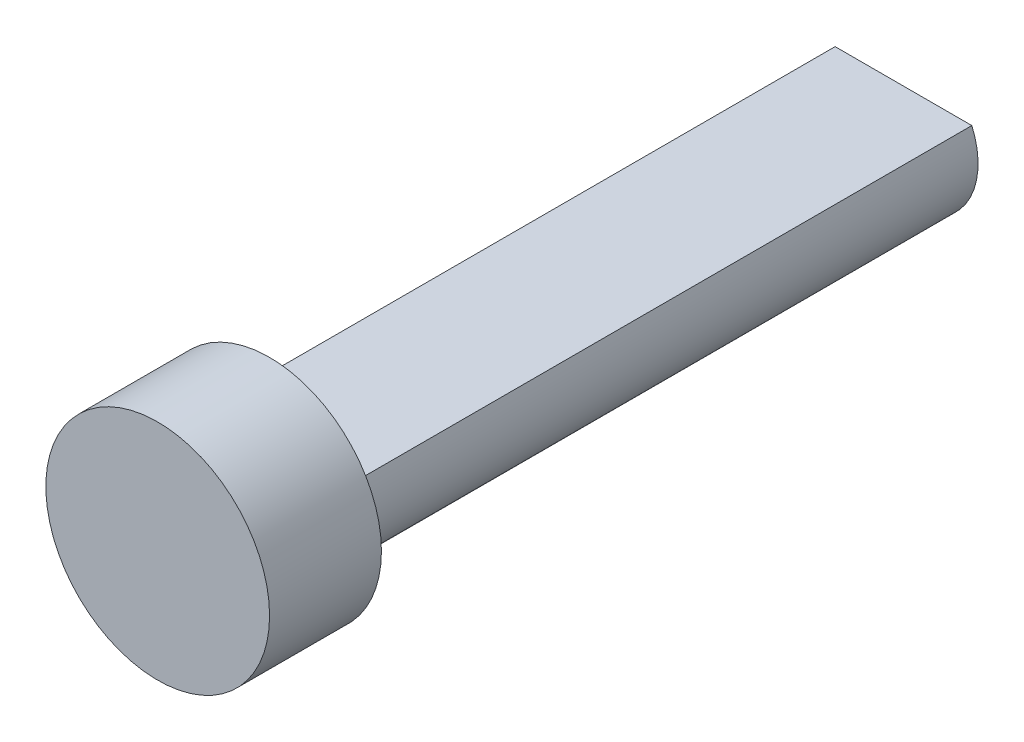
SolidWorks part; units mm, degrees
ref_plane "Front Plane" through (0, 0, 0) normal (0, 0, 1) x (1, 0, 0)
ref_plane "Top Plane" through (0, 0, 0) normal (0, 1, 0) x (1, 0, 0)
ref_plane "Right Plane" through (0, 0, 0) normal (1, 0, 0) x (0, 0, -1)
sketch "Sketch1" plane through (0, 0, 0) normal (0, 0, 1) x (1, 0, 0)
  line L0 (-1.833, 0.8) -> (1.833, 0.8)
  arc A0 (-1.833, 0.8) -> (1.833, 0.8) centre (0, 0) ccw
  dimension "D1" = 4
  dimension "D2" = 0.8
extrude "Boss-Extrude1" add sketch "Sketch1" along normal blind 20
sketch "Sketch2" plane through (0, 0, 20) normal (0, 0, 1) x (1, 0, 0)
  circle A0 centre (0, 0) radius 3
  dimension "D1" = 6
extrude "Boss-Extrude2" add sketch "Sketch2" against normal blind 3 contours A0
equation "\"D2@Sketch1\"=2.8-\"D1@Sketch1\"/2"
